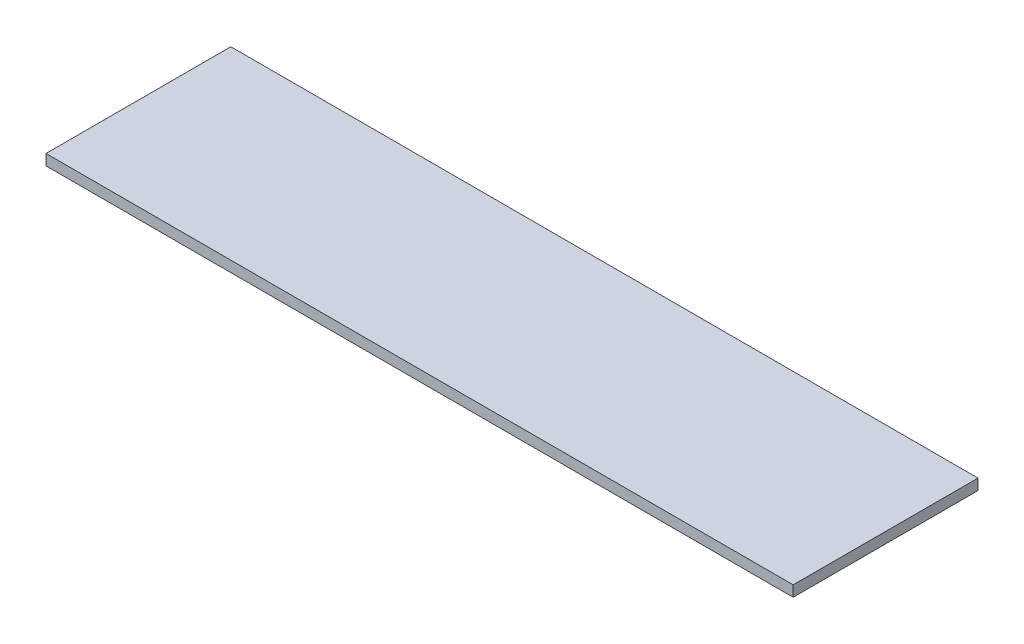
SolidWorks part; units mm, degrees
ref_plane "Front Plane" through (0, 0, 0) normal (0, 0, 1) x (1, 0, 0)
ref_plane "Top Plane" through (0, 0, 0) normal (0, 1, 0) x (1, 0, 0)
ref_plane "Right Plane" through (0, 0, 0) normal (1, 0, 0) x (0, 0, -1)
sketch "Sketch1" plane through (0, 0, 0) normal (0, 1, 0) x (1, 0, 0)
  line L1 (0, 0) -> (138.45, 0)
  line L2 (0, 0) -> (0, 34.25)
  line L3 (0, 34.25) -> (138.45, 34.25)
  line L4 (138.45, 0) -> (138.45, 34.25)
  dimension "D1" = 138.45
  dimension "D2" = 34.25
extrude "Boss-Extrude1" add sketch "Sketch1" along normal blind 2
